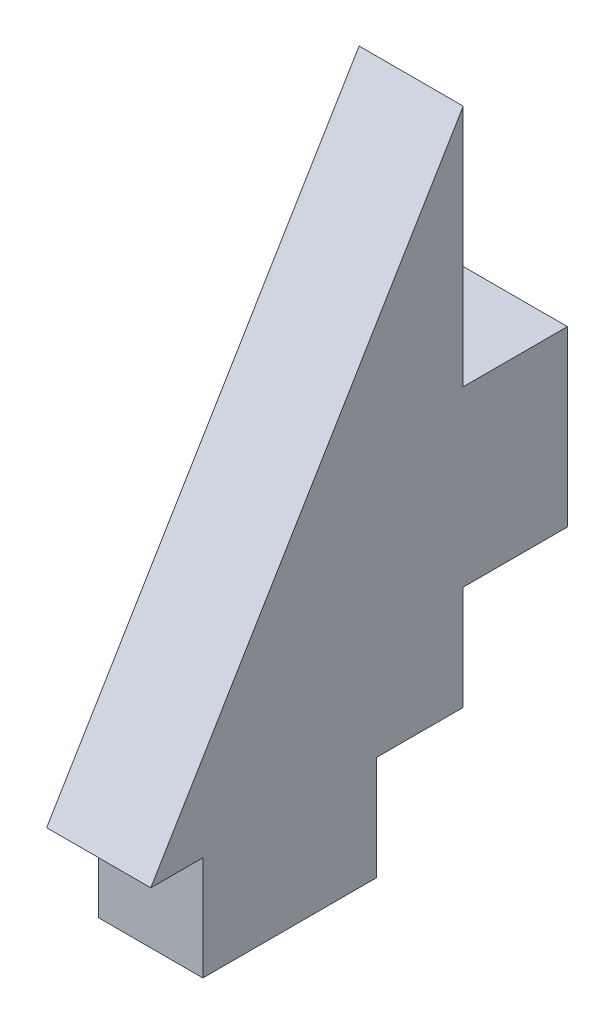
SolidWorks part; units mm, degrees
ref_plane "Front Plane" through (0, 0, 0) normal (0, 0, 1) x (1, 0, 0)
ref_plane "Top Plane" through (0, 0, 0) normal (0, 1, 0) x (1, 0, 0)
ref_plane "Right Plane" through (0, 0, 0) normal (1, 0, 0) x (0, 0, -1)
sketch "Sketch1" plane through (0, 0, 0) normal (1, 0, 0) x (0, 0, -1)
  line L0 (-9, 0) -> (0, 15)
  line L1 (0, 15) -> (0, 0)
  line L2 (0, 0) -> (-9, 0)
  line L4 (-7.5, 0) -> (-2.5, 0)
  line L5 (-7.5, 0) -> (-7.5, -3)
  line L6 (-7.5, -3) -> (-2.5, -3)
  line L7 (-2.5, 0) -> (-2.5, -3)
  line L8 (0, 3) -> (3, 3)
  line L9 (0, 3) -> (0, 8)
  line L10 (0, 8) -> (3, 8)
  line L11 (3, 3) -> (3, 8)
  dimension "D1" = 9
  dimension "D2" = 15
  dimension "D3" = 3
  dimension "D4" = 5
  dimension "D5" = 3
  dimension "D6" = 5
  dimension "D7" = 1.5
  dimension "D8" = 3
extrude "Boss-Extrude1" add sketch "Sketch1" along normal blind 3 contours L2 L1 L0 | L7 L2 L5 L6 | L8 L11 L10 L1
